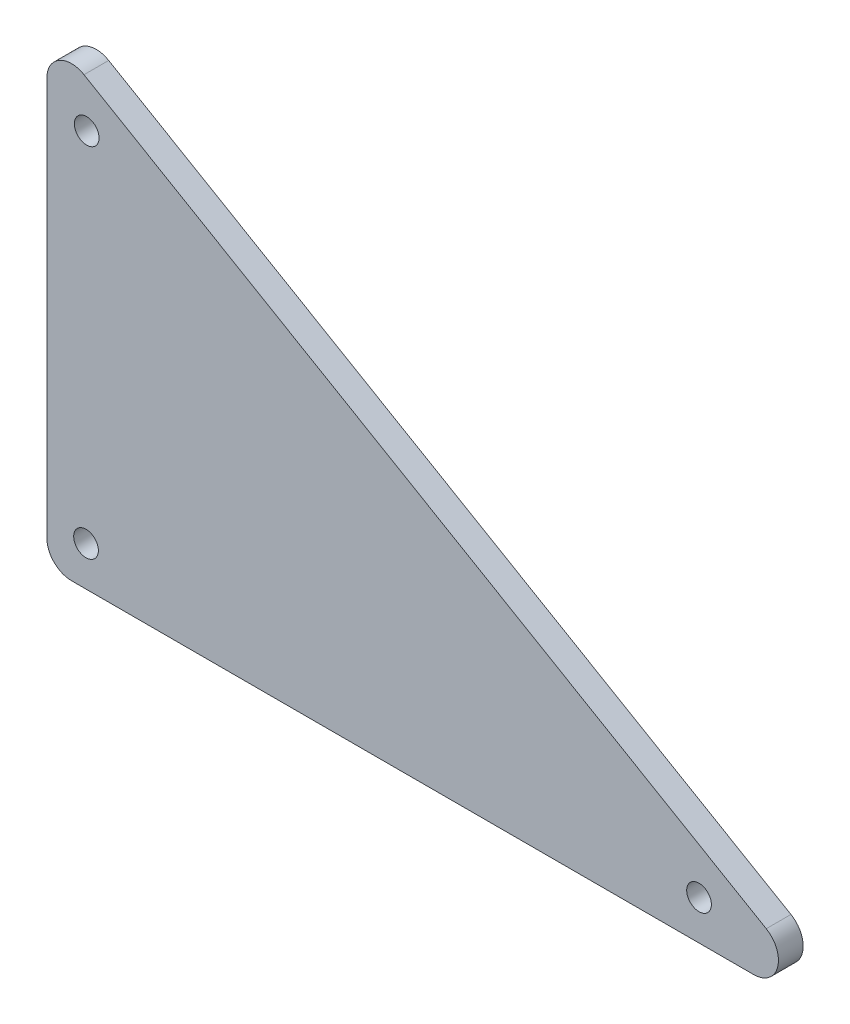
SolidWorks part; units mm, degrees
ref_plane "Plano frontal" through (0, 0, 0) normal (0, 0, 1) x (1, 0, 0)
ref_plane "Plano superior" through (0, 0, 0) normal (0, 1, 0) x (1, 0, 0)
ref_plane "Plano direito" through (0, 0, 0) normal (1, 0, 0) x (0, 0, -1)
sketch "Esboço1" plane through (0, 0, 0) normal (0, 0, 1) x (1, 0, 0)
  line L11 (80.4246, -51.974) -> (-81.2087, -51.974)
  line L12 (-81.2087, -51.974) -> (-81.2087, 42.4329)
  line L13 (-81.2087, 42.4329) -> (80.4246, -51.974)
  circle A0 centre (-73.1422, 28.4567) radius 2.5
  circle A1 centre (50.8648, -43.9733) radius 2.5
  circle A2 centre (-73.2752, -43.9733) radius 2.5
  dimension "D4" = 124.14
  dimension "D3" = 72.43
  dimension "D5" = 143.61
extrude "Ressalto-extrusão1" add sketch "Esboço1" along normal blind 5
fillet "Filete1" radius 5 3 edges at (-81.2087, -51.974, 2.5) (80.4246, -51.974, 2.5) (-81.2087, 42.4329, 2.5)
